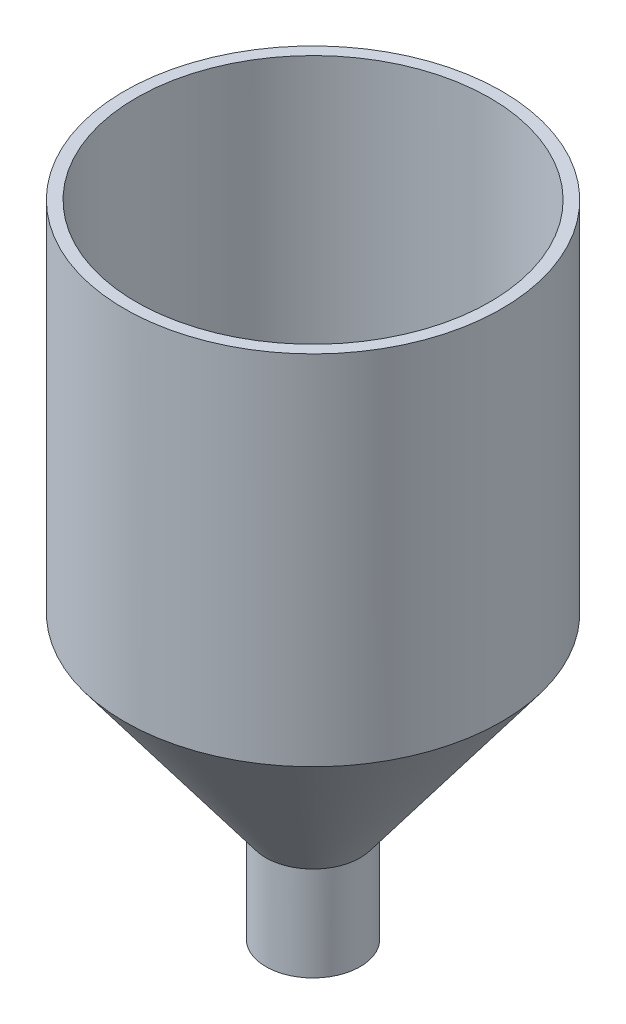
SolidWorks part; units mm, degrees
ref_plane "Plan de face" through (0, 0, 0) normal (0, 0, 1) x (1, 0, 0)
ref_plane "Plan de dessus" through (0, 0, 0) normal (0, 1, 0) x (1, 0, 0)
ref_plane "Plan de droite" through (0, 0, 0) normal (1, 0, 0) x (0, 0, -1)
sketch "Esquisse1" plane through (0, 0, 0) normal (0, 0, 1) x (1, 0, 0)
  line L0 (0, 0) -> (0, 7.8013) construction
  line L1 (-3, 0) -> (-3, 8.3333)
  line L2 (-3, 8.3333) -> (-15, 24.3333)
  line L3 (-15, 24.3333) -> (-15, 54.3333)
  line L4 (-15, 54.3333) -> (-16, 54.3333)
  line L5 (-16, 54.3333) -> (-16, 24)
  line L6 (-16, 24) -> (-4, 8)
  line L7 (-4, 8) -> (-4, 0)
  line L8 (-4, 0) -> (-3, 0)
  point P7 (-15, 33.1394)
  dimension "D1" = 1
  dimension "D2" = 3
  dimension "D3" = 1
  dimension "D4" = 1
  dimension "D5" = 15
  dimension "D6" = 16
  dimension "D7" = 8
  dimension "D8" = 30
revolve "Révolution1" add sketch "Esquisse1" angle 360 about L0
